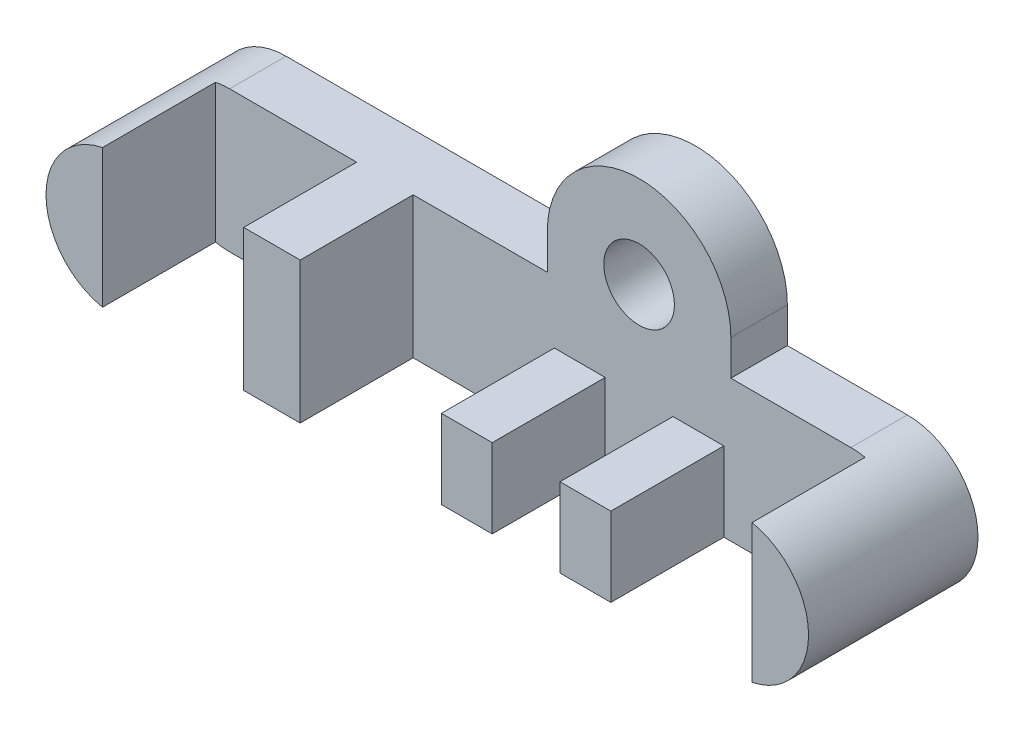
SolidWorks part; units mm, degrees
ref_plane "Front Plane" through (0, 0, 0) normal (0, 0, 1) x (1, 0, 0)
ref_plane "Top Plane" through (0, 0, 0) normal (0, 1, 0) x (1, 0, 0)
ref_plane "Right Plane" through (0, 0, 0) normal (1, 0, 0) x (0, 0, -1)
sketch "Sketch1" plane through (0, 0, 0) normal (0, 0, 1) x (1, 0, 0)
  line L0 (-14.5, -3.75) -> (7.5, -3.75) construction
  line L1 (-14.5, -1.25) -> (-3.25, -1.25)
  line L2 (-14.5, -6.25) -> (7.5, -6.25)
  line L4 (3.25, -1.25) -> (7.5, -1.25)
  line L6 (-3.25, 0) -> (-3.25, -1.25)
  line L8 (3.25, 0) -> (3.25, -1.25)
  circle A0 centre (0, 0) radius 1.25
  arc A1 (3.25, 0) -> (-3.25, 0) centre (0, 0) ccw
  arc A2 (-14.5, -1.25) -> (-14.5, -6.25) centre (-14.5, -3.75) ccw
  arc A3 (7.5, -6.25) -> (7.5, -1.25) centre (7.5, -3.75) ccw
  circle A4 centre (0, 0) radius 3.25 construction
  dimension "D2" = 2.5
  dimension "D4" = 2.5
  dimension "D3" = 22
  dimension "D5" = 7.5
  dimension "D1" = 2
extrude "Boss-Extrude1" add sketch "Sketch1" along normal blind 2
sketch "Sketch2" plane through (0, 0, 2) normal (0, 0, 1) x (1, 0, 0)
  line L0 (-3.25, -1.25) -> (-14.5, -1.25) construction
  line L1 (-3, -1.25) -> (-8, -1.25)
  line L2 (-3, -1.25) -> (-3, -6.25)
  line L3 (-3, -6.25) -> (-8, -6.25)
  line L4 (-8, -1.25) -> (-8, -6.25)
  line L5 (-14.5, -6.25) -> (7.5, -6.25) construction
  line L6 (7.5, -1.25) -> (3.25, -1.25) construction
  line L7 (3, -1.25) -> (7.5, -1.25)
  line L8 (3, -1.25) -> (3, -6.25)
  line L9 (3, -6.25) -> (7.5, -6.25)
  line L10 (8, -1.3005) -> (8, -6.1995)
  line L12 (-10, -1.25) -> (-14.5, -1.25)
  line L13 (-10, -1.25) -> (-10, -6.25)
  line L14 (-10, -6.25) -> (-14.5, -6.25)
  line L15 (-15, -1.3005) -> (-15, -6.1995)
  line L16 (-3.25, -1.25) -> (-14.5, -1.25)
  line L17 (-14.5, -6.25) -> (7.5, -6.25)
  line L18 (7.5, -1.25) -> (3.25, -1.25)
  line L19 (-3.25, -1.25) -> (-14.5, -1.25)
  line L20 (-14.5, -6.25) -> (7.5, -6.25)
  line L21 (7.5, -1.25) -> (3.25, -1.25)
  line L23 (-3.45, 0) -> (-3.45, -3.45)
  line L24 (-3.45, -3.45) -> (3.45, -3.45)
  line L25 (3.45, 0) -> (3.45, -3.45)
  line L26 (3.25, -1.25) -> (3.25, 0)
  line L27 (3.25, -1.25) -> (3.25, 0)
  line L28 (-3.25, 0) -> (-3.25, -1.25)
  line L29 (-3.25, 0) -> (-3.25, -1.25)
  line L30 (-1.2, -3.45) -> (1.2, -3.45)
  line L31 (-1.2, -3.45) -> (-1.2, -6.25)
  line L32 (-1.2, -6.25) -> (1.2, -6.25)
  line L33 (1.2, -3.45) -> (1.2, -6.25)
  circle A2 centre (0, 0) radius 3.25
  circle A3 centre (0, 0) radius 3.45
  arc A5 (3.25, 0) -> (-3.25, 0) centre (0, 0) ccw
  arc A6 (-14.5, -1.25) -> (-14.5, -6.25) centre (-14.5, -3.75) ccw
  arc A7 (7.5, -6.25) -> (7.5, -1.25) centre (7.5, -3.75) ccw
  arc A8 (3.25, 0) -> (-3.25, 0) centre (0, 0) ccw
  arc A9 (-14.5, -1.25) -> (-14.5, -6.25) centre (-14.5, -3.75) ccw
  arc A10 (7.5, -6.25) -> (7.5, -1.25) centre (7.5, -3.75) ccw
  line M19 (-3.25, -1.25) -> (-14.5, -1.25)
  arc M20 (-14.5, -1.25) -> (-14.5, -6.25) centre (-14.5, -3.75) ccw
  line M21 (-14.5, -6.25) -> (7.5, -6.25)
  arc M22 (7.5, -6.25) -> (7.5, -1.25) centre (7.5, -3.75) ccw
  dimension "D1" = 5
  dimension "D2" = 5
  dimension "D5" = 5
  dimension "D6" = 2
  dimension "D7" = 1.8
  dimension "D8" = 1.8
  dimension "D3" = 0
  dimension "D4" = 0.2
extrude "Boss-Extrude2" add sketch "Sketch2" along normal blind 4 contours L31 L24 L2 M21 | L24 L33 L8 M21 | L10 M22 | L15 M20 | L13 L4 M19 M21 | A2 | A8 L19 A9 L20 A10 L21
